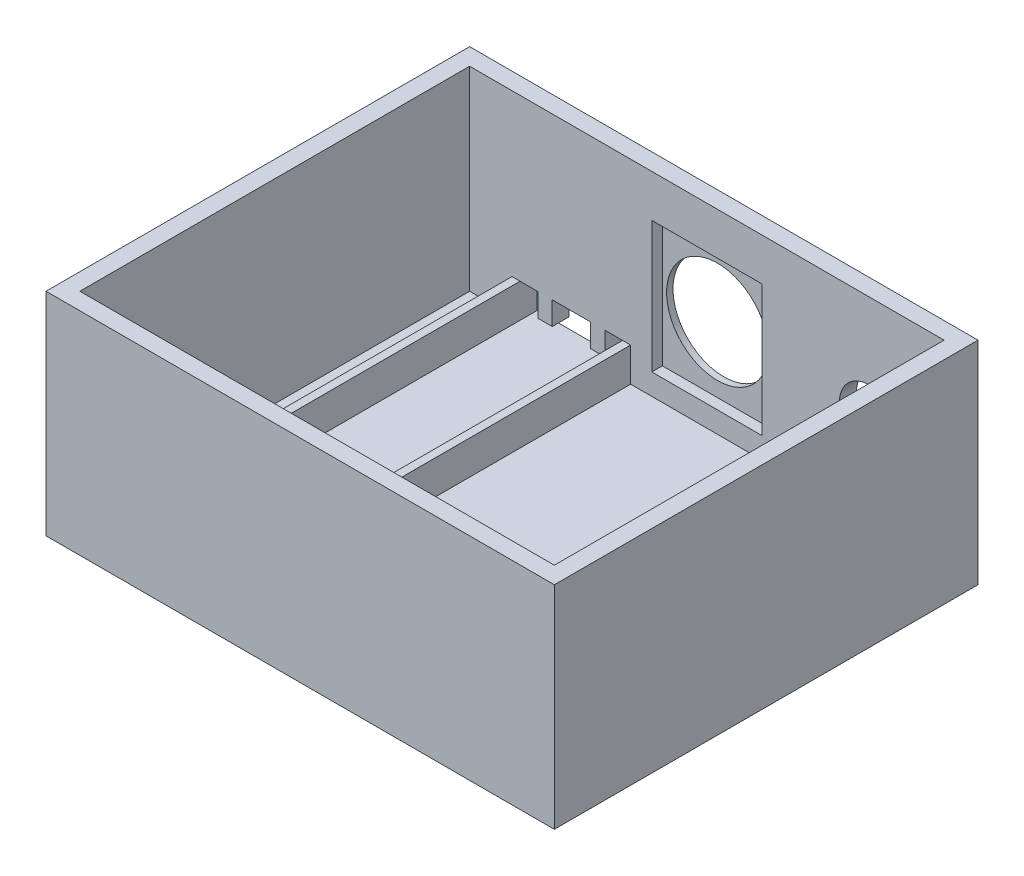
SolidWorks part; units mm, degrees
ref_plane "Front Plane" through (0, 0, 0) normal (0, 0, 1) x (1, 0, 0)
ref_plane "Top Plane" through (0, 0, 0) normal (0, 1, 0) x (1, 0, 0)
ref_plane "Right Plane" through (0, 0, 0) normal (1, 0, 0) x (0, 0, -1)
sketch "Sketch1" plane through (0, 0, 0) normal (0, 1, 0) x (1, 0, 0)
  line L1 (-70.5712, -39.9173) -> (49.4288, -39.9173)
  line L2 (-70.5712, -39.9173) -> (-70.5712, 60.0827)
  line L3 (-70.5712, 60.0827) -> (49.4288, 60.0827)
  line L4 (49.4288, -39.9173) -> (49.4288, 60.0827)
  dimension "D1" = 120
  dimension "D2" = 100
extrude "Boss-Extrude1" add sketch "Sketch1" along normal blind 50
sketch "Sketch2" plane through (0, 50, 0) normal (0, 1, 0) x (1, 0, 0)
  line L0 (49.4288, 60.0827) -> (-70.5712, 60.0827) construction
  line L1 (-66.5712, 56.0827) -> (45.4288, 56.0827)
  line L2 (-66.5712, 56.0827) -> (-66.5712, -35.9173)
  line L3 (-66.5712, -35.9173) -> (45.4288, -35.9173)
  line L4 (45.4288, 56.0827) -> (45.4288, -35.9173)
  line L5 (-70.5712, -39.9173) -> (49.4288, -39.9173) construction
  line L6 (-70.5712, 60.0827) -> (-70.5712, -39.9173) construction
  line L7 (49.4288, -39.9173) -> (49.4288, 60.0827) construction
  dimension "D1" = 4
  dimension "D2" = 4
  dimension "D3" = 4
  dimension "D4" = 4
extrude "Cut-Extrude1" cut sketch "Sketch2" against normal blind 46
sketch "Sketch3" plane through (0, 4, 0) normal (0, 1, 0) x (1, 0, 0)
  line L0 (-66.5712, 56.0827) -> (-66.5712, -35.9173) construction
  line L1 (49.4288, 60.0827) -> (-70.5712, 60.0827) construction
  line L2 (-56.5712, 60.0827) -> (-28.5712, 60.0827)
  line L3 (-56.5712, 60.0827) -> (-56.5712, -9.9173)
  line L4 (-56.5712, -9.9173) -> (-28.5712, -9.9173)
  line L5 (-28.5712, 60.0827) -> (-28.5712, -9.9173)
  dimension "D1" = 28
  dimension "D2" = 70
  dimension "D3" = 10
extrude "Boss-Extrude3" add sketch "Sketch3" along normal blind 8
sketch "Sketch6" plane through (0, 0, 9.9173) normal (0, 0, 1) x (1, 0, 0)
  line L0 (-56.5712, 12) -> (-28.5712, 12) construction
  line L1 (-54.6743, 12) -> (-30.4643, 12)
  line L2 (-54.6743, 12) -> (-54.6743, 4)
  line L3 (-54.6743, 4) -> (-30.4643, 4)
  line L4 (-30.4643, 12) -> (-30.4643, 4)
  line L5 (-66.5712, 4) -> (45.4288, 4) construction
  dimension "D1" = 24.21
extrude "Cut-Extrude4" cut sketch "Sketch6" against normal blind 66
sketch "Sketch7" plane through (0, 0, -56.0827) normal (0, 0, 1) x (1, 0, 0)
  line L0 (-30.4643, 4) -> (-30.4643, 12) construction
  line L1 (-54.6743, 12) -> (-50.4743, 12)
  line L2 (-54.6743, 12) -> (-54.6743, 6.53)
  line L4 (-30.4643, 12) -> (-30.4643, 6.53)
  line L6 (-47.0743, 12) -> (-38.0743, 12)
  line L7 (-38.0743, 6.53) -> (-34.6643, 6.53)
  line L8 (-50.4743, 12) -> (-50.4743, 6.53)
  line L9 (-50.4743, 6.53) -> (-47.0743, 6.53)
  line L10 (-34.6643, 12) -> (-34.6643, 6.53)
  line L11 (-54.6743, 6.53) -> (-54.6743, 4)
  line L12 (-47.0743, 6.53) -> (-47.0743, 12)
  line L13 (-54.6743, 4) -> (-30.4643, 4)
  line L14 (-38.0743, 6.53) -> (-38.0743, 12)
  line L15 (-34.6643, 12) -> (-30.4643, 12)
  line L18 (-30.4643, 6.53) -> (-30.4643, 4)
  dimension "D2" = 4.2
  dimension "D3" = 4.2
  dimension "D4" = 9
  dimension "D5" = 3.4
extrude "Cut-Extrude6" cut sketch "Sketch7" against normal blind 66
sketch "Sketch8" plane through (0, 0, -56.0827) normal (0, 0, 1) x (1, 0, 0)
  line L0 (49.4288, 50) -> (-70.5712, 50) construction
  line L1 (2.4288, 40) -> (-23.5712, 40)
  line L2 (2.4288, 40) -> (2.4288, 9)
  line L3 (2.4288, 9) -> (-23.5712, 9)
  line L4 (-23.5712, 40) -> (-23.5712, 9)
  line L5 (49.4288, 50) -> (49.4288, 0) construction
  dimension "D1" = 31
  dimension "D2" = 26
  dimension "D3" = 10
  dimension "D4" = 47
extrude "Cut-Extrude7" cut sketch "Sketch8" against normal blind 2.5
sketch "Sketch9" plane through (0, 0, -58.5827) normal (0, 0, 1) x (1, 0, 0)
  line L0 (2.4288, 40) -> (-23.5712, 40) construction
  line L1 (2.4288, 9) -> (2.4288, 40) construction
  circle A0 centre (-10.5712, 24.5) radius 12
  point P2 (-10.5712, 40)
  point P5 (2.4288, 24.5)
  dimension "D1" = 15.5
  dimension "D2" = 13
extrude "Cut-Extrude8" cut sketch "Sketch9" against normal blind 2.5
sketch "Sketch10" plane through (0, 0, -60.0827) normal (0, 0, -1) x (-1, 0, 0)
  line L0 (-49.4288, 50) -> (-49.4288, 0) construction
  line L2 (-50.6638, 25) -> (89.3617, 25) construction
  circle A0 centre (-27.7288, 25) radius 7
  dimension "D1" = 21.7
extrude "Cut-Extrude9" cut sketch "Sketch10" against normal blind 12.5
